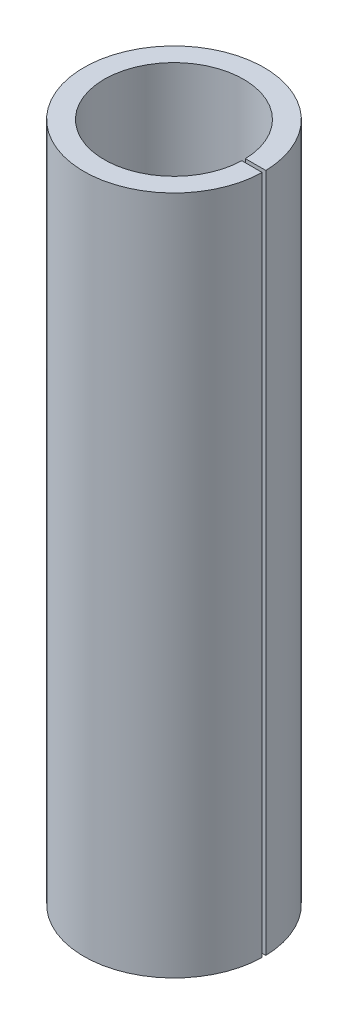
SolidWorks part; units mm, degrees
ref_plane "Front Plane" through (0, 0, 0) normal (0, 0, 1) x (1, 0, 0)
ref_plane "Top Plane" through (0, 0, 0) normal (0, 1, 0) x (1, 0, 0)
ref_plane "Right Plane" through (0, 0, 0) normal (1, 0, 0) x (0, 0, -1)
ref_plane "Plane1" through (0, 0, 0) normal (0, 0, 1) x (1, 0, 0)
sketch "Sketch1" plane through (0, 0, 0) normal (0, 0, 1) x (1, 0, 0)
  line L0 (3.9053, 38.1) -> (3.9053, 0)
  line L1 (3.9053, 0) -> (5.0482, 0)
  line L2 (5.0482, 0) -> (5.0482, 38.1)
  line L3 (5.0482, 38.1) -> (3.9053, 38.1)
  line L4 (0, 0) -> (0, 38.1) construction
  dimension "D1" = 38.1
revolve "Revolve1" add sketch "Sketch1" angle 360 about L4
ref_plane "Plane2" through (0, 0, 0) normal (1, 0, 0) x (0, 0, -1)
sketch "Sketch2" plane through (0, 0, 0) normal (1, 0, 0) x (0, 0, -1)
  line L0 (-0.1, 0) -> (0.1, 0)
  line L1 (0.1, 0) -> (0.1, 38.1)
  line L2 (0.1, 38.1) -> (-0.1, 38.1)
  line L3 (-0.1, 38.1) -> (-0.1, 0)
  dimension "D1" = 38.1
extrude "Cut-Extrude1" cut sketch "Sketch2" along normal blind 5.3
